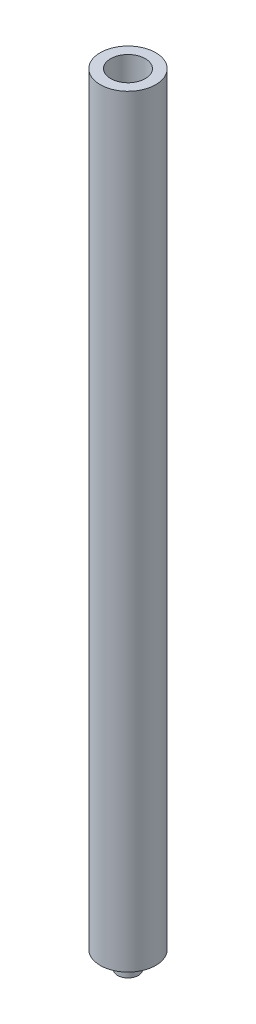
SolidWorks part; units mm, degrees
ref_plane "Front Plane" through (0, 0, 0) normal (0, 0, 1) x (1, 0, 0)
ref_plane "Top Plane" through (0, 0, 0) normal (0, 1, 0) x (1, 0, 0)
ref_plane "Right Plane" through (0, 0, 0) normal (1, 0, 0) x (0, 0, -1)
sketch "Sketch1" plane through (0, 0, 0) normal (0, 1, 0) x (1, 0, 0)
  circle A0 centre (0, 0) radius 4
extrude "Boss-Extrude1" add sketch "Sketch1" against normal blind 40
sketch "Sketch2" plane through (0, -40, 0) normal (0, -1, 0) x (1, 0, 0)
  circle A0 centre (0, 0) radius 1.5
extrude "Boss-Extrude2" add sketch "Sketch2" along normal blind 2.5
sketch "Sketch3" plane through (0, 0, 0) normal (0, 1, 0) x (1, 0, 0)
  circle A0 centre (0, 0) radius 4
extrude "Boss-Extrude3" add sketch "Sketch3" along normal blind 70
sketch "Sketch4" plane through (0, 70, 0) normal (0, 1, 0) x (1, 0, 0)
  circle A0 centre (0, 0) radius 2.5
extrude "Cut-Extrude1" cut sketch "Sketch4" against normal blind 10
